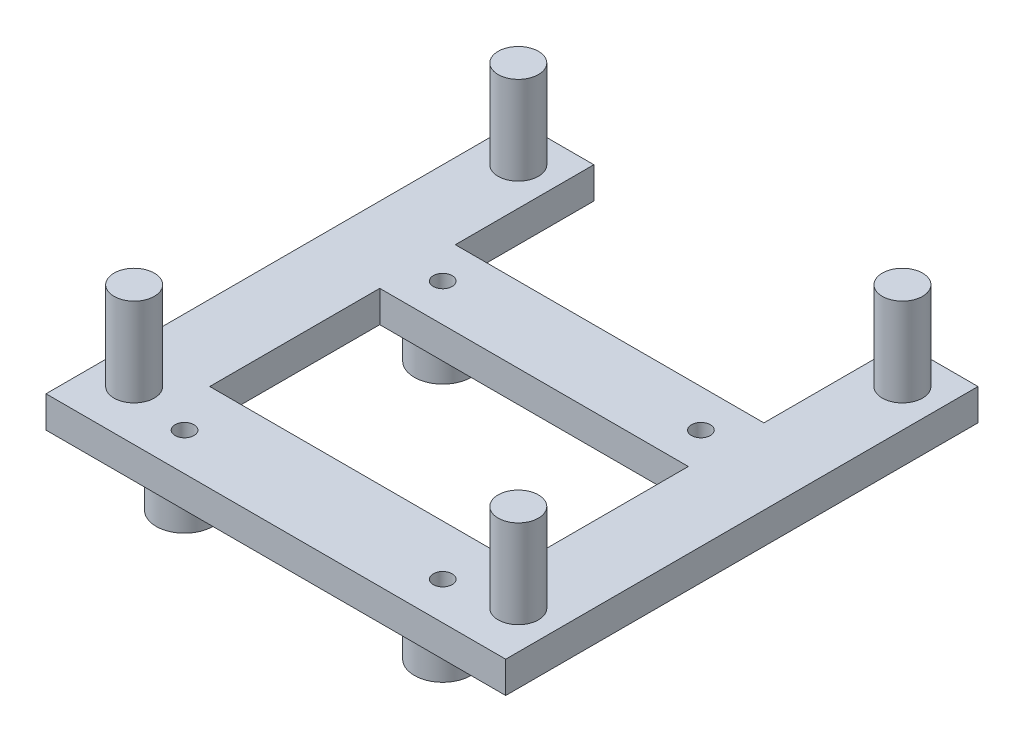
SolidWorks part; units mm, degrees
ref_plane "Front Plane" through (0, 0, 0) normal (0, 0, 1) x (1, 0, 0)
ref_plane "Top Plane" through (0, 0, 0) normal (0, 1, 0) x (1, 0, 0)
ref_plane "Right Plane" through (0, 0, 0) normal (1, 0, 0) x (0, 0, -1)
sketch "Sketch1" plane through (0, 0, 0) normal (0, 1, 0) x (1, 0, 0)
  line L1 (15.25, 15.25) -> (-15.25, 15.25) construction
  line L2 (15.25, 15.25) -> (15.25, -15.25) construction
  line L3 (15.25, -15.25) -> (-15.25, -15.25) construction
  line L4 (-15.25, 15.25) -> (-15.25, -15.25) construction
  line L5 (15.25, 15.25) -> (-15.25, -15.25) construction
  line L6 (15.25, -15.25) -> (-15.25, 15.25) construction
  circle A0 centre (-15.25, -15.25) radius 1.6
  circle A1 centre (-15.25, 15.25) radius 1.6
  circle A2 centre (15.25, 15.25) radius 1.6
  circle A3 centre (15.25, -15.25) radius 1.6
  point P8 (0, 0)
  dimension "D3" = 3.2
  dimension "D1" = 30.5
  dimension "D2" = 30.5
extrude "Boss-Extrude1" add sketch "Sketch1" along normal blind 7
sketch "Sketch2" plane through (0, 0, 0) normal (0, -1, 0) x (1, 0, 0)
  line L3 (-12.25, 12.25) -> (12.25, 12.25)
  line L6 (-18.25, 19.25) -> (-18.25, -18.25)
  line L7 (-18.25, -18.25) -> (-12.25, -18.25)
  line L8 (-12.25, 12.25) -> (-12.25, -18.25)
  line L9 (18.25, 19.25) -> (-18.25, 19.25)
  line L10 (18.25, 19.25) -> (18.25, -18.25)
  line L11 (18.25, -18.25) -> (12.25, -18.25)
  line L12 (12.25, 12.25) -> (12.25, -18.25)
  circle A0 centre (-15.25, -15.25) radius 1.6 construction
  circle A1 centre (15.25, -15.25) radius 1.6 construction
  circle A2 centre (-15.25, 15.25) radius 1.6 construction
  dimension "D1" = 3
  dimension "D2" = 3
  dimension "D4" = 3
  dimension "D5" = 3
  dimension "D8" = 4
  dimension "D3" = 6
  dimension "D6" = 6
  dimension "D7" = 3
extrude "Boss-Extrude2" add sketch "Sketch2" along normal blind 2.5
sketch "Sketch3" plane through (0, -2.5, 0) normal (0, -1, 0) x (1, 0, 0)
  line L0 (-18.25, 19.25) -> (-18.25, -18.25) construction
  line L1 (18.25, 19.25) -> (-18.25, 19.25) construction
  line L3 (-10.25, 16.25) -> (10.25, 16.25) construction
  line L4 (-10.25, 16.25) -> (-10.25, -4.25) construction
  line L5 (-10.25, -4.25) -> (10.25, -4.25) construction
  line L6 (10.25, 16.25) -> (10.25, -4.25) construction
  circle A0 centre (-10.25, 16.25) radius 0.75
  circle A1 centre (10.25, 16.25) radius 0.75
  circle A2 centre (-10.25, -4.25) radius 0.75
  circle A3 centre (10.25, -4.25) radius 0.75
  circle A4 centre (-10.25, 16.25) radius 2.25
  circle A5 centre (10.25, 16.25) radius 2.25
  circle A6 centre (10.25, -4.25) radius 2.25
  circle A7 centre (-10.25, -4.25) radius 2.25
  dimension "D1" = 20.5
  dimension "D2" = 8
  dimension "D3" = 3
  dimension "D4" = 1.5
  dimension "D5" = 4.5
  dimension "D6" = 2
  dimension "D7" = 2
extrude "Boss-Extrude3" add sketch "Sketch3" along normal blind 3
sketch "Sketch4" plane through (0, -2.5, 0) normal (0, 1, 0) x (1, 0, 0)
  line L0 (-12.25, 18.25) -> (-12.25, -12.25) construction
  line L1 (-12.25, 7.25) -> (12.25, 7.25)
  line L2 (-12.25, 7.25) -> (-12.25, 1.25)
  line L3 (-12.25, 1.25) -> (12.25, 1.25)
  line L4 (12.25, 7.25) -> (12.25, 1.25)
  line L5 (12.25, -12.25) -> (12.25, 18.25) construction
  circle A0 centre (-10.25, 4.25) radius 1.25 construction
  dimension "D1" = 6
  dimension "D2" = 3
extrude "Boss-Extrude4" add sketch "Sketch4" along normal up to surface (2.5 mm away) contours L1 L4 L3 L2 up to face at (15.25, 0, 16.85)
sketch "Sketch5" plane through (0, -2.5, 0) normal (0, -1, 0) x (1, 0, 0)
  circle A0 centre (-10.25, 16.25) radius 0.75
  circle A1 centre (10.25, 16.25) radius 0.75
  circle A2 centre (10.25, -4.25) radius 0.75
  circle A3 centre (-10.25, -4.25) radius 0.75
  circle A4 centre (-10.25, 16.25) radius 0.75 construction
extrude "Cut-Extrude1" cut sketch "Sketch5" against normal blind 10
